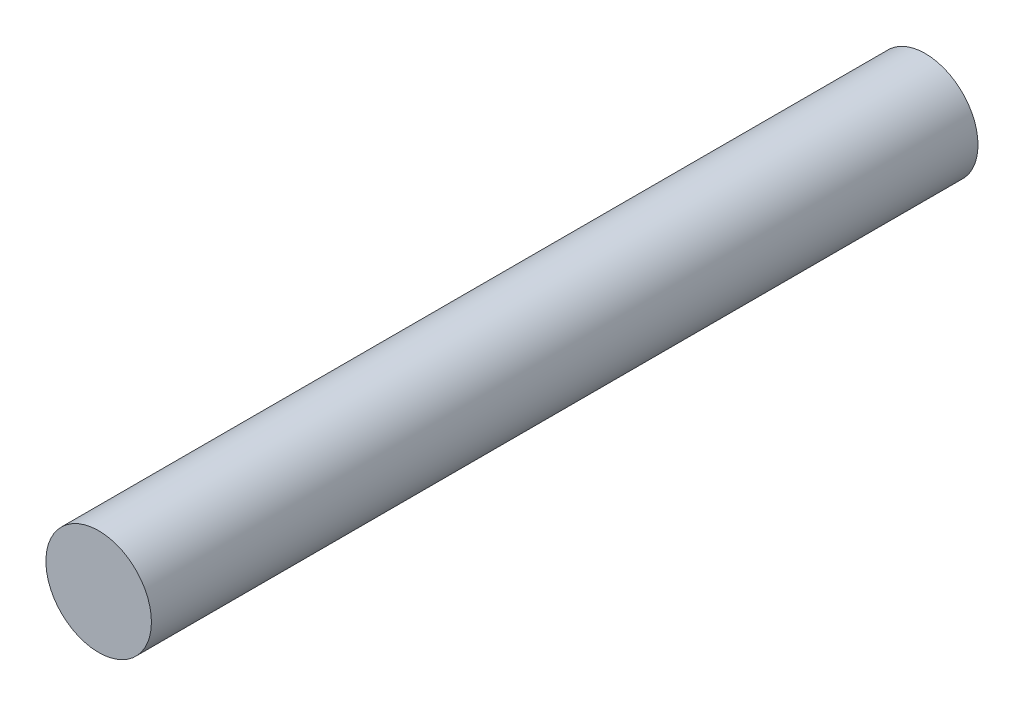
SolidWorks part; units mm, degrees
ref_plane "Front Plane" through (0, 0, 0) normal (0, 0, 1) x (1, 0, 0)
ref_plane "Top Plane" through (0, 0, 0) normal (0, 1, 0) x (1, 0, 0)
ref_plane "Right Plane" through (0, 0, 0) normal (1, 0, 0) x (0, 0, -1)
sketch "Sketch1" plane through (0, 0, 0) normal (0, 0, 1) x (1, 0, 0)
  circle A0 centre (0, 0) radius 0.75
  dimension "D1" = 1.5
extrude "Boss-Extrude1" add sketch "Sketch1" along normal blind 19.5
sketch "Sketch2" plane through (0, 0, 19.5) normal (0, 0, 1) x (1, 0, 0)
  circle A0 centre (0, 0) radius 1.5
  dimension "D1" = 3
extrude "Boss-Extrude2" add sketch "Sketch2" against normal blind 19.5
sketch "Sketch3" plane through (0, 0, 0) normal (0, 0, -1) x (-1, 0, 0)
  circle A0 centre (0, 0) radius 1.5
sketch "Sketch4" plane through (0, 0, 0) normal (0, 0, -1) x (-1, 0, 0)
  circle A0 centre (0, 0) radius 1.5
extrude "Boss-Extrude3" add sketch "Sketch4" along normal blind 4
